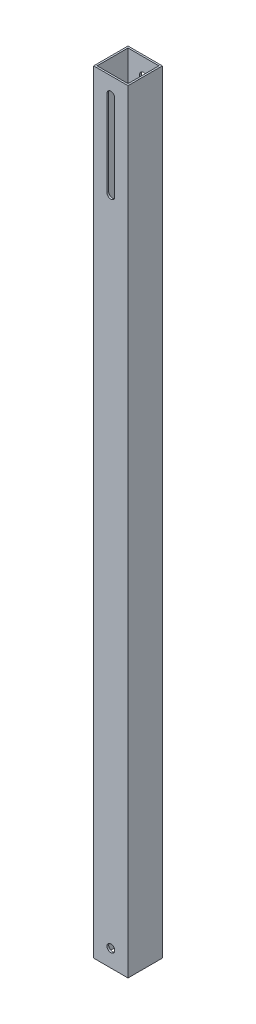
SolidWorks part; units mm, degrees
ref_plane "Front Plane" through (0, 0, 0) normal (0, 0, 1) x (1, 0, 0)
ref_plane "Top Plane" through (0, 0, 0) normal (0, 1, 0) x (1, 0, 0)
ref_plane "Right Plane" through (0, 0, 0) normal (1, 0, 0) x (0, 0, -1)
sketch "Sketch1" plane through (0, 0, 0) normal (0, 1, 0) x (1, 0, 0)
  line L0 (-9, -9) -> (-9, 9)
  line L1 (-10, -10) -> (10, -10)
  line L2 (-10, -10) -> (-10, 10)
  line L3 (-10, 10) -> (10, 10)
  line L4 (10, -10) -> (10, 10)
  line L5 (-10, -10) -> (10, 10) construction
  line L6 (-10, 10) -> (10, -10) construction
  line L7 (-9, 9) -> (9, 9)
  line L8 (9, -9) -> (9, 9)
  line L9 (-9, -9) -> (9, -9)
  point P0 (0, 0)
  dimension "D1" = 20
  dimension "D2" = 20
  dimension "D3" = 1
extrude "Boss-Extrude1" add sketch "Sketch1" along normal blind 450
sketch "Sketch2" plane through (0, 0, 10) normal (0, 0, 1) x (1, 0, 0)
  line L0 (-10, 0) -> (10, 0) construction
  line L1 (0, 440) -> (0, 390) construction
  line L2 (2.25, 440) -> (2.25, 390)
  line L3 (-2.25, 440) -> (-2.25, 390)
  line L4 (-10, 450) -> (10, 450) construction
  circle A0 centre (0, 10) radius 2.25
  arc A1 (2.25, 440) -> (-2.25, 440) centre (0, 440) ccw
  arc A2 (-2.25, 390) -> (2.25, 390) centre (0, 390) ccw
  point P7 (0, 415)
  point P12 (0, 287.9214)
  point P13 (0, 255.0551)
  point P14 (0, 0)
  dimension "D1" = 4.5
  dimension "D3" = 10
  dimension "D2" = 10
  dimension "D4" = 60
  dimension "D5" = 4.5
extrude "Cut-Extrude1" cut sketch "Sketch2" against normal through all
